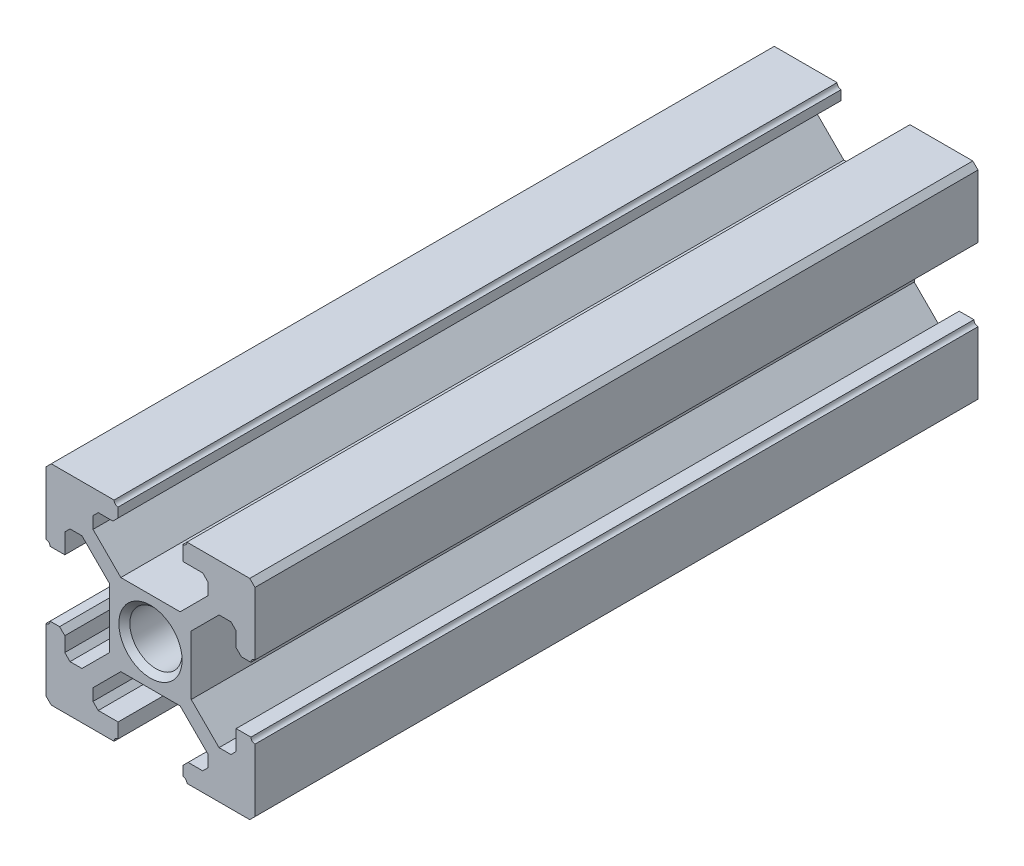
SolidWorks part; units mm, degrees
ref_plane "Front Plane" through (0, 0, 0) normal (0, 0, 1) x (1, 0, 0)
ref_plane "Top Plane" through (0, 0, 0) normal (0, 1, 0) x (1, 0, 0)
ref_plane "Right Plane" through (0, 0, 0) normal (1, 0, 0) x (0, 0, -1)
sketch "Sketch1" plane through (0, 0, 0) normal (0, 0, 1) x (1, 0, 0)
  line L0 (0, 10.7337) -> (0, 0.7337) construction
  line L1 (-9.5, 10) -> (-3.4865, 10)
  line L2 (-10, 9.5) -> (-10, 3.4865)
  line L3 (-9.5, -10) -> (-3.4865, -10)
  line L4 (10, 9.5) -> (10, 3.4865)
  line L5 (-9.75, 9.75) -> (9.75, -9.75) construction
  line L6 (-9.75, -9.75) -> (10, 10) construction
  line L7 (0, 0) -> (-10, 0) construction
  line L8 (3.1, 9.6135) -> (3.1, 8.2)
  line L9 (3.1, 8.2) -> (5, 8.2)
  line L10 (5.5, 7.7) -> (5.5, 6.5607)
  line L11 (5.5, 6.5607) -> (2.8393, 3.9)
  line L12 (2.8393, 3.9) -> (0, 3.9)
  line L13 (3.9, 2.8393) -> (3.9, 0)
  line L14 (6.5607, 5.5) -> (3.9, 2.8393)
  line L15 (9.6135, 3.1) -> (8.7, 3.1)
  line L16 (8.2, 3.6) -> (8.2, 5)
  line L17 (7.7, 5.5) -> (6.5607, 5.5)
  line L18 (3.4865, 10) -> (9.5, 10)
  line L19 (10, -3.4865) -> (10, -9.5)
  line L20 (5, 8.2) -> (5.5, 7.7)
  line L21 (8.2, 5) -> (7.7, 5.5)
  line L22 (9.5, 10) -> (10, 9.5)
  line L23 (8.7, 3.1) -> (8.2, 3.6)
  line L24 (3.9, -2.8393) -> (3.9, 0)
  line L25 (6.5607, -5.5) -> (3.9, -2.8393)
  line L26 (7.7, -5.5) -> (6.5607, -5.5)
  line L27 (8.2, -5) -> (7.7, -5.5)
  line L28 (8.2, -3.1) -> (8.2, -5)
  line L29 (9.6135, -3.1) -> (8.2, -3.1)
  line L30 (10, -3.4865) -> (10, -9.5)
  line L31 (10, -9.5) -> (9.5, -10)
  line L32 (9.5, -10) -> (3.4865, -10)
  line L33 (3.1, -9.6135) -> (3.1, -8.7)
  line L34 (3.1, -8.7) -> (3.6, -8.2)
  line L35 (3.6, -8.2) -> (5, -8.2)
  line L36 (5, -8.2) -> (5.5, -7.7)
  line L37 (5.5, -7.7) -> (5.5, -6.5607)
  line L38 (5.5, -6.5607) -> (2.8393, -3.9)
  line L39 (2.8393, -3.9) -> (0, -3.9)
  line L40 (-2.8393, -3.9) -> (0, -3.9)
  line L41 (-5.5, -6.5607) -> (-2.8393, -3.9)
  line L42 (-5.5, -7.7) -> (-5.5, -6.5607)
  line L43 (-5, -8.2) -> (-5.5, -7.7)
  line L44 (-3.1, -8.2) -> (-5, -8.2)
  line L45 (-3.1, -9.6135) -> (-3.1, -8.2)
  line L46 (-3.4865, -10) -> (-9.5, -10)
  line L47 (-9.5, -10) -> (-10, -9.5)
  line L48 (-10, -9.5) -> (-10, -3.4865)
  line L49 (-9.6135, -3.1) -> (-8.7, -3.1)
  line L50 (-8.7, -3.1) -> (-8.2, -3.6)
  line L51 (-8.2, -3.6) -> (-8.2, -5)
  line L52 (-8.2, -5) -> (-7.7, -5.5)
  line L53 (-7.7, -5.5) -> (-6.5607, -5.5)
  line L54 (-6.5607, -5.5) -> (-3.9, -2.8393)
  line L55 (-3.9, -2.8393) -> (-3.9, 0)
  line L56 (-3.9, 2.8393) -> (-3.9, 0)
  line L57 (-6.5607, 5.5) -> (-3.9, 2.8393)
  line L58 (-7.7, 5.5) -> (-6.5607, 5.5)
  line L59 (-8.2, 5) -> (-7.7, 5.5)
  line L60 (-8.2, 3.1) -> (-8.2, 5)
  line L61 (-9.6135, 3.1) -> (-8.2, 3.1)
  line L62 (-10, 3.4865) -> (-10, 9.5)
  line L63 (-10, 9.5) -> (-9.5, 10)
  line L64 (-9.5, 10) -> (-3.4865, 10)
  line L65 (-3.1, 9.6135) -> (-3.1, 8.7)
  line L66 (-3.1, 8.7) -> (-3.6, 8.2)
  line L67 (-3.6, 8.2) -> (-5, 8.2)
  line L68 (-5, 8.2) -> (-5.5, 7.7)
  line L69 (-5.5, 7.7) -> (-5.5, 6.5607)
  line L70 (-5.5, 6.5607) -> (-2.8393, 3.9)
  line L71 (-2.8393, 3.9) -> (0, 3.9)
  line L72 (3.4865, -10) -> (9.5, -10)
  line L73 (-10, -3.4865) -> (-10, -9.5)
  arc A0 (3.1, 9.6135) -> (3.4865, 10) centre (3.1, 10) ccw
  arc A1 (9.6135, 3.1) -> (10, 3.4865) centre (10, 3.1) cw
  arc A2 (9.6135, -3.1) -> (10, -3.4865) centre (10, -3.1) ccw
  arc A3 (3.1, -9.6135) -> (3.4865, -10) centre (3.1, -10) cw
  arc A4 (-3.1, -9.6135) -> (-3.4865, -10) centre (-3.1, -10) ccw
  arc A5 (-9.6135, -3.1) -> (-10, -3.4865) centre (-10, -3.1) cw
  arc A6 (-9.6135, 3.1) -> (-10, 3.4865) centre (-10, 3.1) ccw
  arc A7 (-3.1, 9.6135) -> (-3.4865, 10) centre (-3.1, 10) cw
  point P0 (0, 0)
  point P13 (5.5, 8.2)
  point P17 (3.1, 8.9068)
  point P22 (8.2, 3.1)
  point P23 (8.2, 5.5)
  point P103 (0, 0)
  dimension "D3" = 1.8
  dimension "D4" = 6.1
  dimension "D5" = 11
  dimension "D6" = 6.2
  dimension "D7" = 1.5
extrude "Boss-Extrude1" add sketch "Sketch1" along normal blind 69.2 contours L65 A7 L1 L63 L2 A6 L61 L60 L59 L58 L57 L56 L55 L54 L53 L52 L51 L50 L49 A5 L48 L47 L3 A4 L45 L44 L43 L42 L41 L40 L39 L38 L37 L36 L35 L34 L33 A3 L32 L31 L19 A2 L29 L28 L27 L26 L25 L24 L13 L14 L17
hole_wizard "M6x1.0 Tapped Hole1" positions "3DSketch1" profile "Sketch2" tap size "M6x1.0" standard "ANSI Metric"
sketch3d "3DSketch1"
  line L0 (3.9, -2.8393, 69.2) -> (3.9, 2.8393, 69.2) construction
  line L1 (2.8393, 3.9, 69.2) -> (-2.8393, 3.9, 69.2) construction
  point P0 (0, 0, 0)
  point P3 (0, 0, 0)
  point P5 (0, 0, 0)
  point P7 (0.9996, -8.1302, 0)
  point P9 (0, 0, 0)
  point P11 (0, 0, 69.2)
  dimension "D1" = 3.9
  dimension "D2" = 3.9
sketch "Sketch2" plane through (0, 0, 69.2) normal (1, 0, 0) x (0, -1, 0)
  line L0 (0, 0) -> (0, 30)
  line L1 (0, 30) -> (2.5, 28.4978)
  line L2 (2.5, 28.4978) -> (2.5, 0.525)
  line L3 (2.5, 0.525) -> (3.025, 0)
  line L5 (3.025, 0) -> (0, 0)
  line L6 (-2.5, 0.525) -> (-3.025, 0) construction
  line L10 (0, 30) -> (-2.5, 28.4978) construction
  line L11 (0, -6.35) -> (0, 107.95) construction
  dimension "Tap Drill Dia." = 5
  dimension "Tap Drill Depth" = 30
  dimension "Near C'Sink Dia." = 6.05
  dimension "Near C'Sink Angle" = 90
  dimension "Drill Angle" = 118
cosmetic thread "Hole Thread6"
hole_wizard "M6x1.0 Tapped Hole2" positions "3DSketch2" profile "Sketch3" tap size "M6x1.0" standard "ANSI Metric"
sketch3d "3DSketch2"
  line L0 (2.8393, 3.9, 0) -> (-2.8393, 3.9, 0) construction
  line L1 (3.9, -2.8393, 0) -> (3.9, 2.8393, 0) construction
  point P3 (0, 0, 0)
  dimension "D1" = 3.9
  dimension "D2" = 3.9
sketch "Sketch3" plane through (0, 0, 0) normal (1, 0, 0) x (0, 1, 0)
  line L0 (0, 0) -> (0, 30)
  line L1 (0, 30) -> (2.5, 28.4978)
  line L2 (2.5, 28.4978) -> (2.5, 0.525)
  line L3 (2.5, 0.525) -> (3.025, 0)
  line L5 (3.025, 0) -> (0, 0)
  line L6 (-2.5, 0.525) -> (-3.025, 0) construction
  line L10 (0, 30) -> (-2.5, 28.4978) construction
  line L11 (0, -6.35) -> (0, 107.95) construction
  dimension "Tap Drill Dia." = 5
  dimension "Tap Drill Depth" = 30
  dimension "Near C'Sink Dia." = 6.05
  dimension "Near C'Sink Angle" = 90
  dimension "Drill Angle" = 118
cosmetic thread "Hole Thread7"
